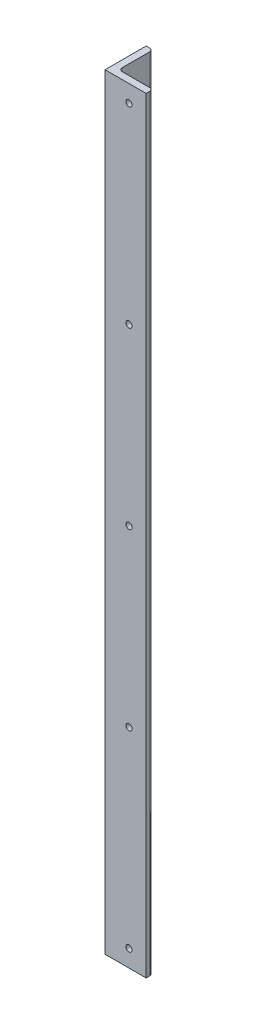
SolidWorks part; units mm, degrees
material "6061 Alloy"
ref_plane "Front Plane" through (0, 0, 0) normal (0, 0, 1) x (1, 0, 0)
ref_plane "Top Plane" through (0, 0, 0) normal (0, 1, 0) x (1, 0, 0)
ref_plane "Right Plane" through (0, 0, 0) normal (1, 0, 0) x (0, 0, -1)
sketch "Sketch2" plane through (0, 0, 0) normal (0, 1, 0) x (1, 0, 0)
  line L0 (0, 0) -> (19.05, 0)
  line L1 (0, 0) -> (0, 19.05)
  line L2 (4.7625, 3.175) -> (17.4625, 3.175)
  line L3 (3.175, 4.7625) -> (3.175, 17.4625)
  line L4 (0, 19.05) -> (1.5875, 19.05)
  line L5 (19.05, 1.5875) -> (19.05, 0)
  line L6 (3.175, 3.175) -> (3.175, 19.05) construction
  line L7 (3.175, 3.175) -> (19.05, 3.175) construction
  arc A0 (3.175, 17.4625) -> (1.5875, 19.05) centre (1.5875, 17.4625) ccw
  arc A1 (3.175, 4.7625) -> (4.7625, 3.175) centre (4.7625, 4.7625) ccw
  arc A2 (17.4625, 3.175) -> (19.05, 1.5875) centre (17.4625, 1.5875) cw
  dimension "D2" = 1.5875
  dimension "D1" = 3.175
extrude "Boss-Extrude1" add sketch "Sketch2" along normal blind 355.6
sketch "Sketch3" plane through (0, 0, -3.175) normal (0, 0, -1) x (-1, 0, 0)
  line L0 (-19.05, 0) -> (-3.175, 0) construction
  line L1 (-11.1125, 0) -> (-11.1125, 15.875) construction
  line L2 (-19.05, 355.6) -> (-3.175, 355.6) construction
  line L3 (-11.1125, 355.6) -> (-11.1125, 339.725) construction
  line L4 (-11.1125, 15.875) -> (-11.1125, 177.8) construction
  line L5 (-11.1125, 177.8) -> (-11.1125, 339.725) construction
  circle A0 centre (-11.1125, 7.9375) radius 1.4224
  circle A1 centre (-11.1125, 347.6625) radius 1.4224
  circle A2 centre (-11.1125, 96.8375) radius 1.4224
  circle A3 centre (-11.1125, 177.8) radius 1.4224
  circle A4 centre (-11.1125, 258.7625) radius 1.4224
  point P16 (-11.1125, 177.8)
  point P17 (-11.1125, 96.8375)
  point P19 (-11.1125, 258.7625)
  dimension "D1" = 2.8448
  dimension "D2" = 2.8448
  dimension "D3" = 2.8448
  dimension "D4" = 2.8448
  dimension "D5" = 2.8448
extrude "Cut-Extrude1" cut sketch "Sketch3" against normal blind 5.08
